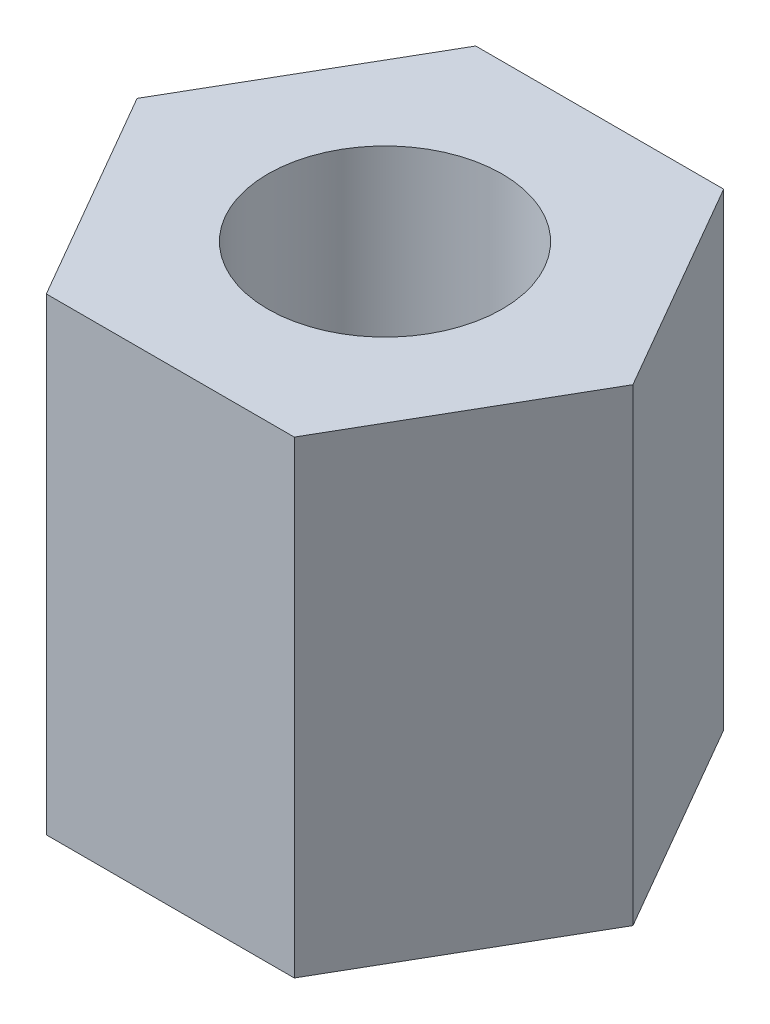
SolidWorks part; units mm, degrees
ref_plane "Спереди" through (0, 0, 0) normal (0, 0, 1) x (1, 0, 0)
ref_plane "Сверху" through (0, 0, 0) normal (0, 1, 0) x (1, 0, 0)
ref_plane "Справа" through (0, 0, 0) normal (1, 0, 0) x (0, 0, -1)
sketch "Эскиз1" plane through (0, 0, 0) normal (0, 1, 0) x (1, 0, 0)
  line L1 (3.1754, 0) -> (1.5877, 2.75)
  line L2 (1.5877, 2.75) -> (-1.5877, 2.75)
  line L3 (-1.5877, 2.75) -> (-3.1754, 0)
  line L4 (-3.1754, 0) -> (-1.5877, -2.75)
  line L5 (-1.5877, -2.75) -> (1.5877, -2.75)
  line L6 (1.5877, -2.75) -> (3.1754, 0)
  circle A0 centre (0, 0) radius 2.75 construction
  circle A1 centre (0, 0) radius 1.5
  dimension "D1" = 5.5
extrude "Бобышка-Вытянуть1" add sketch "Эскиз1" along normal blind 6
